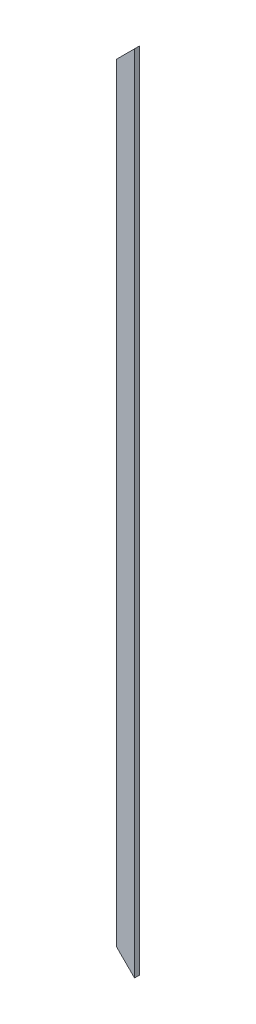
SolidWorks part; units mm, degrees
material "Oak"
ref_plane "Front Plane" through (0, 0, 0) normal (0, 0, 1) x (1, 0, 0)
ref_plane "Top Plane" through (0, 0, 0) normal (0, 1, 0) x (1, 0, 0)
ref_plane "Right Plane" through (0, 0, 0) normal (1, 0, 0) x (0, 0, -1)
sketch "Sketch1" plane through (0, 0, 0) normal (0, 1, 0) x (1, 0, 0)
  line L1 (-69.85, -19.05) -> (69.85, -19.05)
  line L2 (-69.85, -19.05) -> (-69.85, 19.05)
  line L3 (-69.85, 19.05) -> (69.85, 19.05)
  line L4 (69.85, -19.05) -> (69.85, 19.05)
  line L5 (-69.85, -19.05) -> (69.85, 19.05) construction
  line L6 (-69.85, 19.05) -> (69.85, -19.05) construction
  point P0 (0, 0)
  dimension "D1" = 38.1
  dimension "D2" = 139.7
extrude "Boss-Extrude1" add sketch "Sketch1" along normal blind 6273.8 contours L1 L4 L3 L2
sketch "Sketch2" plane through (0, 0, 19.05) normal (0, 0, 1) x (1, 0, 0)
  line L0 (69.85, 6273.8) -> (-69.85, 6134.1)
  line L1 (-69.85, 6273.8) -> (-69.85, 0) construction
  line L2 (-69.85, 6134.1) -> (-69.85, 6273.8)
  line L3 (-69.85, 6273.8) -> (69.85, 6273.8)
  line L4 (69.85, 0) -> (-69.85, 139.7)
  line L5 (-69.85, 139.7) -> (-69.85, 0)
  line L6 (-69.85, 0) -> (69.85, 0)
extrude "Cut-Extrude1" cut sketch "Sketch2" against normal through all both and the other way through all
